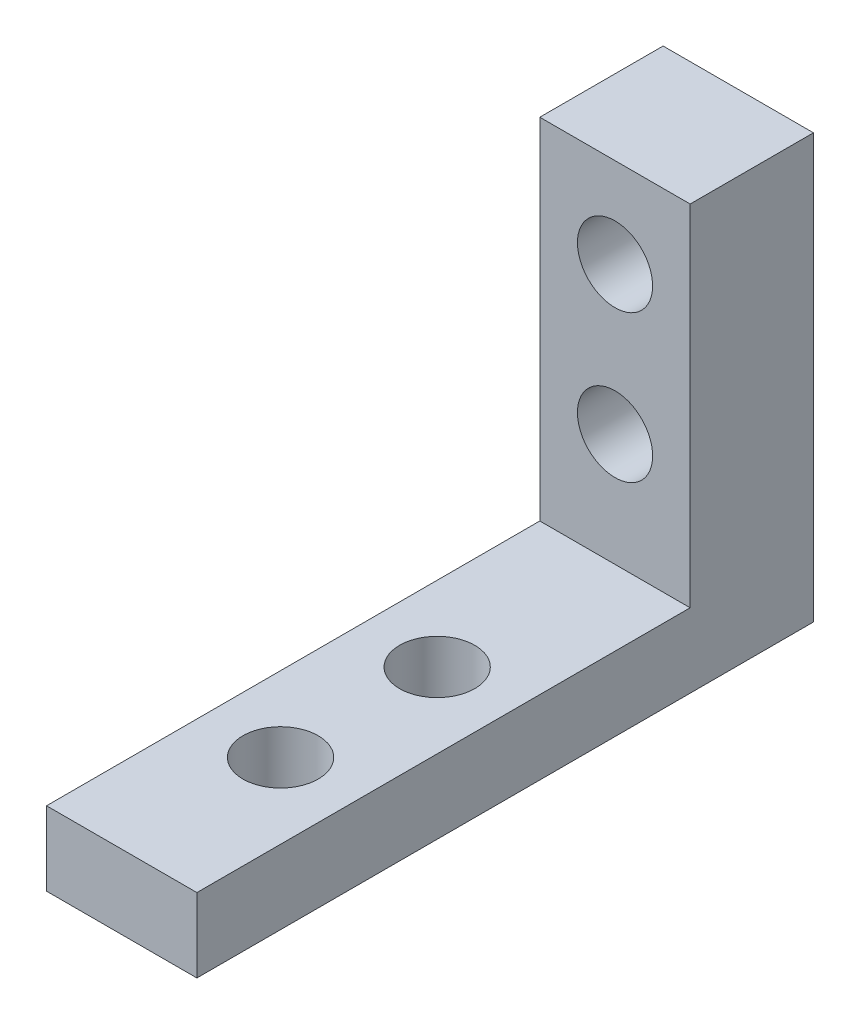
SolidWorks part; units mm, degrees
ref_plane "Front Plane" through (0, 0, 0) normal (0, 0, 1) x (1, 0, 0)
ref_plane "Top Plane" through (0, 0, 0) normal (0, 1, 0) x (1, 0, 0)
ref_plane "Right Plane" through (0, 0, 0) normal (1, 0, 0) x (0, 0, -1)
sketch "Sketch2" plane through (0, 0, 0) normal (1, 0, 0) x (0, 0, -1)
  line L0 (0, 0) -> (0, 14.1783)
  line L1 (0, 14.1783) -> (5, 14.1783)
  line L2 (5, 14.1783) -> (5, -3)
  line L3 (5, -3) -> (-20, -3)
  line L4 (0, 0) -> (-20, 0)
  line L5 (-20, 0) -> (-20, -3)
  dimension "D1" = 5
  dimension "D2" = 3
  dimension "D3" = 25
extrude "Boss-Extrude2" add sketch "Sketch2" along normal blind 6.096
sketch "Sketch3" plane through (0, 0, -5) normal (0, 0, -1) x (-1, 0, 0)
  line L1 (0, -3) -> (0, 14.1783) construction
  circle A0 centre (-3.05, 10.5387) radius 1.524
  circle A1 centre (-3.05, 4.5729) radius 1.525
  dimension "D1" = 3.048
  dimension "D3" = 3.05
  dimension "D2" = 3.05
  dimension "D4" = 3.05
extrude "Cut-Extrude1" cut sketch "Sketch3" against normal through all
sketch "Sketch4" plane through (0, 0, 0) normal (0, 1, 0) x (1, 0, 0)
  line L0 (6.096, 0) -> (6.096, -20) construction
  circle A0 centre (3.046, -7.2068) radius 1.524
  circle A1 centre (3.046, -13.5568) radius 1.525
  dimension "D1" = 3.048
  dimension "D3" = 3.05
  dimension "D2" = 3.05
  dimension "D4" = 3.05
  dimension "D5" = 6.35
extrude "Cut-Extrude3" cut sketch "Sketch4" against normal through all
equation "\"3.05im\"=2.74891"
